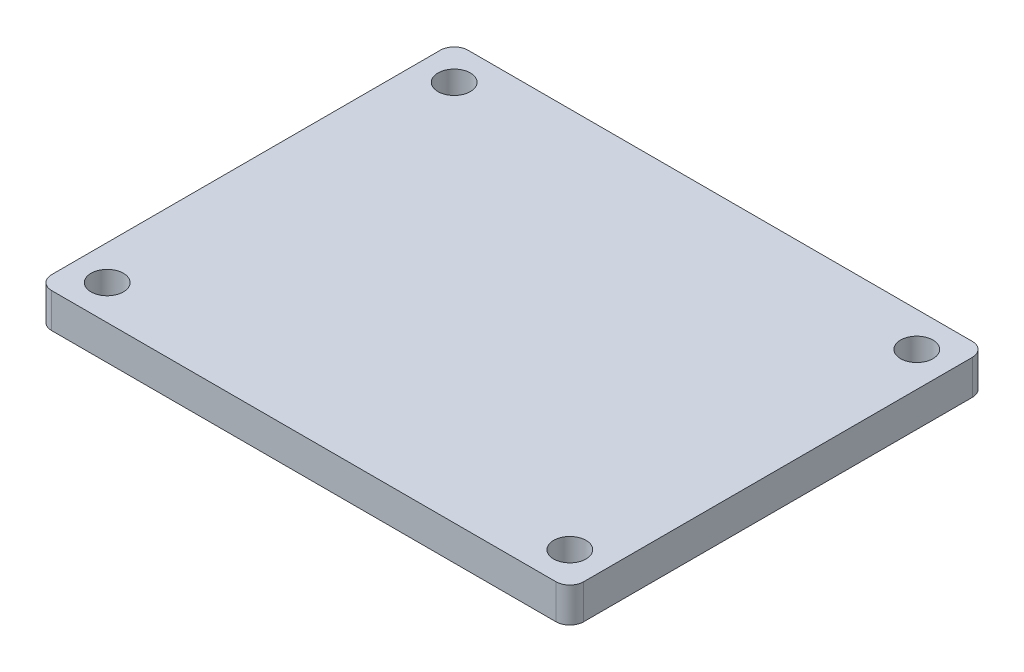
SolidWorks part; units mm, degrees
ref_plane "Front Plane" through (0, 0, 0) normal (0, 0, 1) x (1, 0, 0)
ref_plane "Top Plane" through (0, 0, 0) normal (0, 1, 0) x (1, 0, 0)
ref_plane "Right Plane" through (0, 0, 0) normal (1, 0, 0) x (0, 0, -1)
sketch "Sketch1" plane through (0, 0, 0) normal (0, 1, 0) x (1, 0, 0)
  line L1 (54.5, -45) -> (-54.5, -45)
  line L2 (57.5, -42) -> (57.5, 42)
  line L3 (54.5, 45) -> (-54.5, 45)
  line L4 (-57.5, -42) -> (-57.5, 42)
  line L5 (57.5, -45) -> (-57.5, 45) construction
  line L6 (57.5, 45) -> (-57.5, -45) construction
  arc A0 (57.5, 42) -> (54.5, 45) centre (54.5, 42) ccw
  arc A1 (54.5, -45) -> (57.5, -42) centre (54.5, -42) ccw
  arc A2 (-54.5, -45) -> (-57.5, -42) centre (-54.5, -42) cw
  arc A3 (-54.5, 45) -> (-57.5, 42) centre (-54.5, 42) ccw
  point P0 (0, 0)
  dimension "D3" = 3
  dimension "D1" = 115
  dimension "D2" = 90
extrude "Boss-Extrude1" add sketch "Sketch1" along normal blind 7.5
sketch "Sketch2" plane through (0, 7.5, 0) normal (0, 1, 0) x (1, 0, 0)
  line L1 (50, -37.5) -> (-50, -37.5) construction
  line L2 (50, -37.5) -> (50, 37.5) construction
  line L3 (50, 37.5) -> (-50, 37.5) construction
  line L4 (-50, -37.5) -> (-50, 37.5) construction
  line L5 (50, -37.5) -> (-50, 37.5) construction
  line L6 (50, 37.5) -> (-50, -37.5) construction
  point P0 (0, 0)
  point P7 (-50, 37.5)
  point P8 (50, 37.5)
  point P9 (50, -37.5)
  point P10 (-50, -37.5)
  dimension "D1" = 75
  dimension "D2" = 100
hole_wizard "M6 Clearance Hole1" positions "Sketch3" profile "Sketch5" hole size "M6" standard "ANSI Metric" end condition through all
sketch "Sketch3" plane through (0, 7.5, 0) normal (0, 1, 0) x (1, 0, 0)
  point P1 (-50, 37.5)
  point P5 (50, 37.5)
  point P8 (50, -37.5)
  point P11 (-50, -37.5)
sketch "Sketch5" plane through (-50, 7.5, -37.5) normal (1, 0, 0) x (0, 0, 1)
  line L0 (0, 0) -> (0, 7.5)
  line L1 (0, 7.5) -> (3.5, 7.5)
  line L2 (3.5, 7.5) -> (3.5, 0)
  line L5 (3.5, 0) -> (0, 0)
  line L11 (0, -6.35) -> (0, 107.95) construction
  dimension "Thru Hole Dia." = 7
  dimension "Thru Hole Depth" = 7.5
